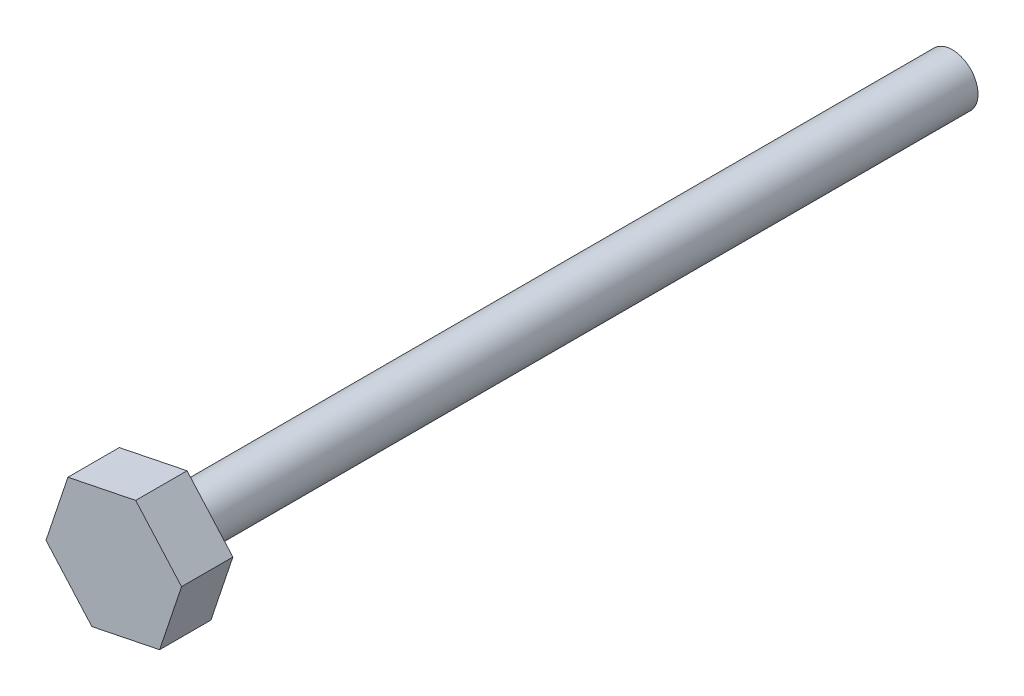
SolidWorks part; units mm, degrees
ref_plane "Front Plane" through (0, 0, 0) normal (0, 0, 1) x (1, 0, 0)
ref_plane "Top Plane" through (0, 0, 0) normal (0, 1, 0) x (1, 0, 0)
ref_plane "Right Plane" through (0, 0, 0) normal (1, 0, 0) x (0, 0, -1)
sketch "Sketch1" plane through (0, 0, 0) normal (0, 0, 1) x (1, 0, 0)
  circle A0 centre (0, 0) radius 1.5
  dimension "D1" = 3
extrude "Boss-Extrude1" add sketch "Sketch1" along normal blind 46
sketch "Sketch2" plane through (0, 0, 46) normal (0, 0, 1) x (1, 0, 0)
  line L1 (1.2813, 3.8329) -> (-2.6788, 3.0261)
  line L2 (-2.6788, 3.0261) -> (-3.9601, -0.8068)
  line L3 (-3.9601, -0.8068) -> (-1.2813, -3.8329)
  line L4 (-1.2813, -3.8329) -> (2.6788, -3.0261)
  line L5 (2.6788, -3.0261) -> (3.9601, 0.8068)
  line L6 (3.9601, 0.8068) -> (1.2813, 3.8329)
  circle A0 centre (0, 0) radius 3.5 construction
  dimension "D1" = 3.5
extrude "Boss-Extrude2" add sketch "Sketch2" along normal blind 3
